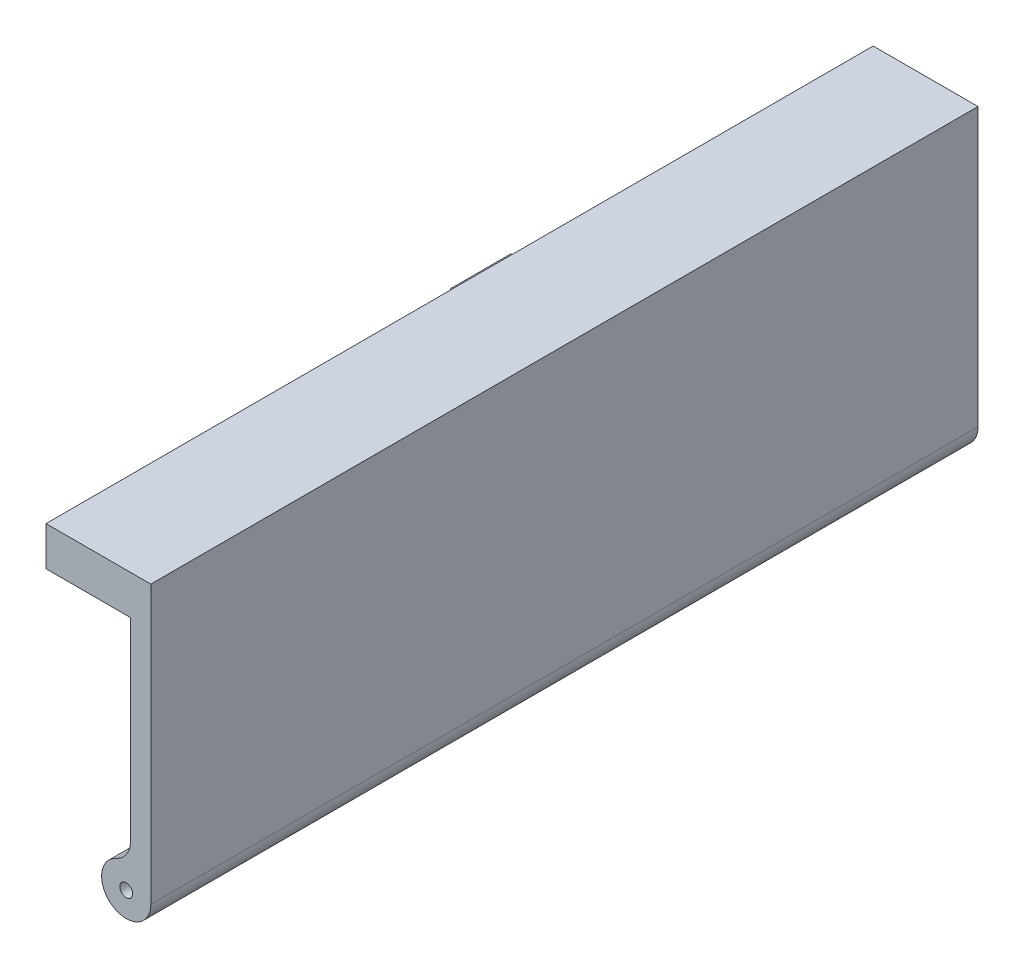
SolidWorks part; units mm, degrees
ref_plane "Front Plane" through (0, 0, 0) normal (0, 0, 1) x (1, 0, 0)
ref_plane "Top Plane" through (0, 0, 0) normal (0, 1, 0) x (1, 0, 0)
ref_plane "Right Plane" through (0, 0, 0) normal (1, 0, 0) x (0, 0, -1)
sketch "Sketch1" plane through (0, 0, 0) normal (0, 0, 1) x (1, 0, 0)
  line L0 (0, 0) -> (3.1723, 0) construction
  line L1 (2.44, 0) -> (2.44, 25)
  line L2 (0.44, 4.49) -> (0.44, 25)
  line L3 (0.44, 25) -> (2.44, 25)
  circle A0 centre (0, 0) radius 0.64
  arc A1 (-1.0175, 2.2177) -> (2.44, 0) centre (0, 0) ccw
  arc A2 (0.44, 4.49) -> (-1.0175, 2.2177) centre (-2.06, 4.49) cw
  dimension "D1" = 1.28
  dimension "D2" = 4.88
  dimension "D5" = 2.5
  dimension "D3" = 25
  dimension "D4" = 2
extrude "Boss-Extrude1" add sketch "Sketch1" along normal blind 82
sketch "Sketch3" plane through (0, 25, 0) normal (0, 1, 0) x (1, 0, 0)
  line L1 (0.44, -82) -> (2.44, -82)
  line L2 (0.44, -82) -> (0.44, 0)
  line L3 (0.44, 0) -> (2.44, 0)
  line L4 (2.44, -82) -> (2.44, 0)
extrude "Boss-Extrude4" add sketch "Sketch3" along normal blind 2.5
sketch "Sketch6" plane through (0.44, 0, 0) normal (-1, 0, 0) x (0, 0, 1)
  line L1 (82, 27.5) -> (0, 27.5)
  line L2 (82, 27.5) -> (82, 23.6193)
  line L3 (82, 23.6193) -> (0, 23.6193)
  line L4 (0, 27.5) -> (0, 23.6193)
  dimension "D1" = 23.01
extrude "Boss-Extrude5" add sketch "Sketch6" along normal blind 8.39
ref_plane "Plane2" through (-7.95, 23.6193, 0) normal (0, 0, 1) x (1, 0, 0)
ref_plane "Plane3" through (-7.95, 23.6193, 82) normal (0, 0, 1) x (1, 0, 0)
sketch "Sketch26" plane through (0, 23.6193, 0) normal (0, -1, 0) x (1, 0, 0)
  line L0 (-7.95, 0) -> (-7.95, 82) construction
  line L1 (-7.95, 33.9228) -> (-5.95, 33.9228)
  line L2 (-7.95, 33.9228) -> (-7.95, 39.9228)
  line L3 (-7.95, 39.9228) -> (-5.95, 39.9228)
  line L4 (-5.95, 33.9228) -> (-5.95, 39.9228)
  line L5 (-6.95, 39.9228) -> (-6.95, 33.9228) construction
  line L6 (-7.95, 36.9228) -> (-5.95, 36.9228) construction
  point P280 (-6.95, 36.9228)
  dimension "D1" = 2
sketch "Sketch27" plane through (-7.95, 0, 0) normal (-1, 0, 0) x (0, 0, 1)
  line L0 (39.9228, 23.6193) -> (33.9228, 23.6193) construction
  line L1 (39.9228, 23.6193) -> (33.9228, 23.6193)
  line L2 (39.9228, 23.6193) -> (39.9228, 25.6193)
  line L3 (39.9228, 25.6193) -> (33.9228, 25.6193)
  line L4 (33.9228, 23.6193) -> (33.9228, 25.6193)
  dimension "D1" = 2
extrude "Boss-Extrude6" add sketch "Sketch27" along normal blind 2
extrude "Cut-Extrude2" cut sketch "Sketch26" against normal blind 2
chamfer "Chamfer1" distance 0.5 angle 45 1 edges at (-7.95, 23.6193, 36.9228)
